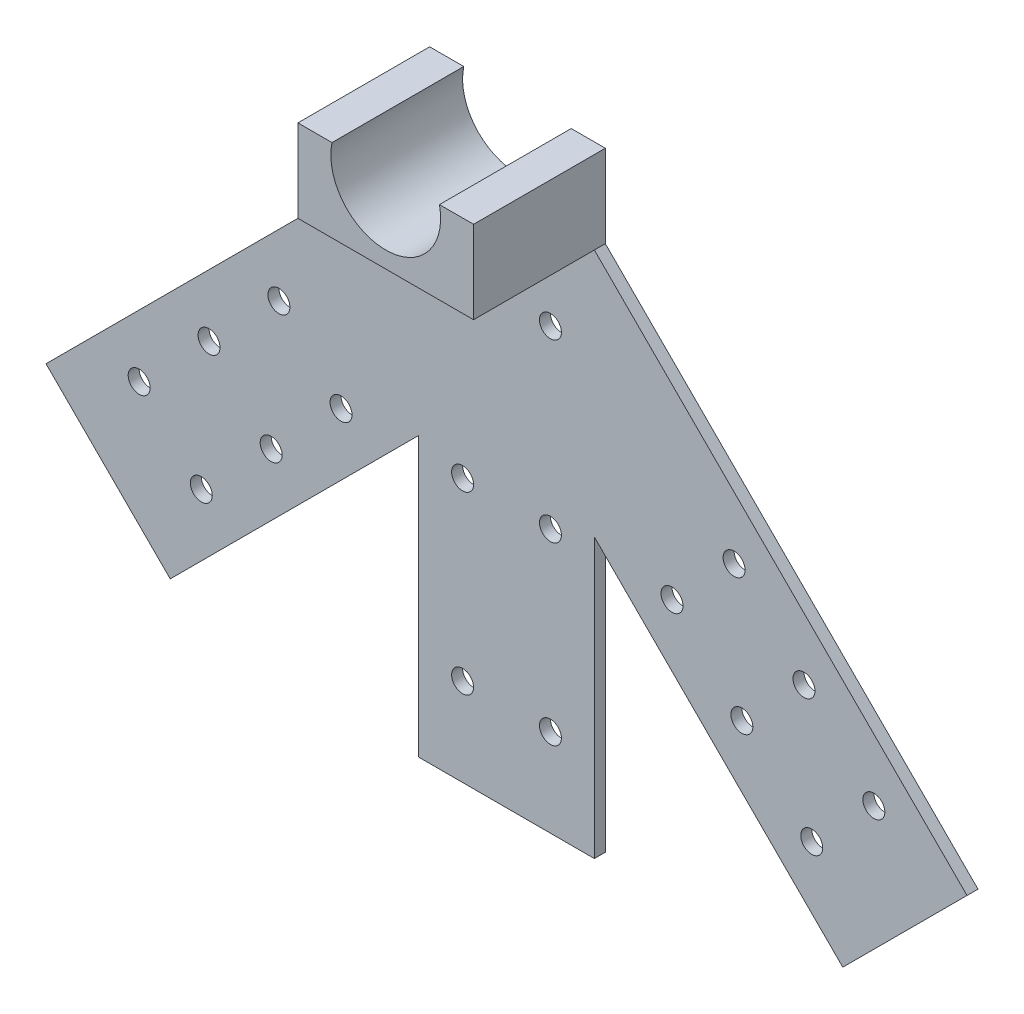
SolidWorks part; units mm, degrees
material "Malleable Cast Iron"
ref_plane "Front Plane" through (0, 0, 0) normal (0, 0, 1) x (1, 0, 0)
ref_plane "Top Plane" through (0, 0, 0) normal (0, 1, 0) x (1, 0, 0)
ref_plane "Right Plane" through (0, 0, 0) normal (1, 0, 0) x (0, 0, -1)
sketch "Sketch2" plane through (0, 0, 0) normal (0, 0, 1) x (1, 0, 0)
  line L0 (-50.8, 0) -> (50.8, 0)
  line L1 (50.8, 0) -> (50.8, 161.1159)
  line L2 (50.8, 161.1159) -> (194.4841, 17.4318)
  line L3 (194.4841, 17.4318) -> (266.3261, 89.2739)
  line L4 (266.3261, 89.2739) -> (50.8, 304.8)
  line L5 (50.8, 304.8) -> (-50.8, 304.8)
  line L6 (0, 304.8) -> (0, 0) construction
  line L7 (230.4051, 53.3528) -> (0, 283.758) construction
  line L8 (-230.4051, 53.3528) -> (0, 283.758) construction
  line L9 (-266.3261, 89.2739) -> (-50.8, 304.8)
  line L10 (-194.4841, 17.4318) -> (-266.3261, 89.2739)
  line L11 (-50.8, 161.1159) -> (-194.4841, 17.4318)
  line L12 (-50.8, 0) -> (-50.8, 161.1159)
  circle A0 centre (212.4446, 107.2344) radius 6.35
  circle A1 centre (172.0335, 147.6455) radius 6.35
  circle A2 centre (131.6223, 188.0567) radius 6.35
  circle A3 centre (136.1124, 111.7245) radius 6.35
  circle A4 centre (95.7013, 152.1356) radius 6.35
  circle A5 centre (176.5236, 71.3133) radius 6.35
  circle A6 centre (25.4, 50.8) radius 6.35
  circle A7 centre (25.4, 152.4) radius 6.35
  circle A8 centre (25.4, 254) radius 6.35
  circle A9 centre (-25.4, 254) radius 6.35
  circle A10 centre (-25.4, 152.4) radius 6.35
  circle A11 centre (-25.4, 50.8) radius 6.35
  circle A12 centre (-176.5236, 71.3133) radius 6.35
  circle A13 centre (-95.7013, 152.1356) radius 6.35
  circle A14 centre (-136.1124, 111.7245) radius 6.35
  circle A15 centre (-131.6223, 188.0567) radius 6.35
  circle A16 centre (-172.0335, 147.6455) radius 6.35
  circle A17 centre (-212.4446, 107.2344) radius 6.35
  dimension "D9" = 12.7
  dimension "D14" = 12.7
  dimension "D15" = 3
  dimension "D1" = 50.8
  dimension "D2" = 101.6
  dimension "D3" = 304.8
  dimension "D4" = 50.8
  dimension "D5" = 304.8
  dimension "D6" = 45
  dimension "D7" = 25.4
  dimension "D8" = 50.8
  dimension "D11" = 57.15
  dimension "D12" = 50.8
  dimension "D13" = 25.4
  dimension "D16" = 101.6
  dimension "D10" = 3
extrude "Boss-Extrude1" add sketch "Sketch2" along normal blind 6.35
sketch "Sketch3" plane through (0, 304.8, 0) normal (0, 1, 0) x (1, 0, 0)
  line L5 (-50.8, 0) -> (50.8, 0)
  line L6 (-50.8, 0) -> (-50.8, -76.2)
  line L7 (-50.8, -76.2) -> (50.8, -76.2)
  line L8 (50.8, 0) -> (50.8, -76.2)
  dimension "D1" = 76.2
  dimension "D2" = 101.6
extrude "Boss-Extrude3" add sketch "Sketch3" along normal blind 47.8
sketch "Sketch4" plane through (0, 0, 76.2) normal (0, 0, 1) x (1, 0, 0)
  line L1 (0, 352.6) -> (0, 304.8) construction
  line L2 (-50.8, 352.6) -> (50.8, 352.6) construction
  line L3 (-50.8, 304.8) -> (50.8, 304.8) construction
  line L4 (-31.0681, 352.6) -> (31.0681, 352.6)
  arc A0 (-31.0681, 352.6) -> (31.0681, 352.6) centre (0, 346.0551) ccw
  dimension "D1" = 31.75
  dimension "D2" = 19.7319
extrude "Cut-Extrude1" cut sketch "Sketch4" against normal through all
sketch "Sketch5" plane through (0, 352.6, 0) normal (0, 1, 0) x (1, 0, 0)
  line L0 (0, -76.2) -> (0, 0) construction
  line L3 (-40.9341, -28.4) -> (-40.9341, -76.2) construction
  line L5 (-50.8, -76.2) -> (-31.0681, -76.2) construction
  line L6 (-44.5041, -18.1) -> (-37.3641, -18.1) construction
  line L7 (-50.8, 0) -> (-266.3261, 0) construction
  circle A1 centre (-40.9341, -18.1) radius 3.57
  circle A2 centre (-40.9341, -18.1) radius 6.57
  circle A3 centre (-40.9341, -58.1) radius 6.57
  circle A4 centre (-40.9341, -58.1) radius 3.57
  circle A5 centre (40.9341, -58.1) radius 6.57
  circle A6 centre (40.9341, -58.1) radius 3.57
  circle A7 centre (40.9341, -18.1) radius 6.57
  circle A8 centre (40.9341, -18.1) radius 3.57
  dimension "D1" = 7.14
  dimension "D2" = 6.57
  dimension "D4" = 2
  dimension "D3" = 18.1
  dimension "D5" = 40
